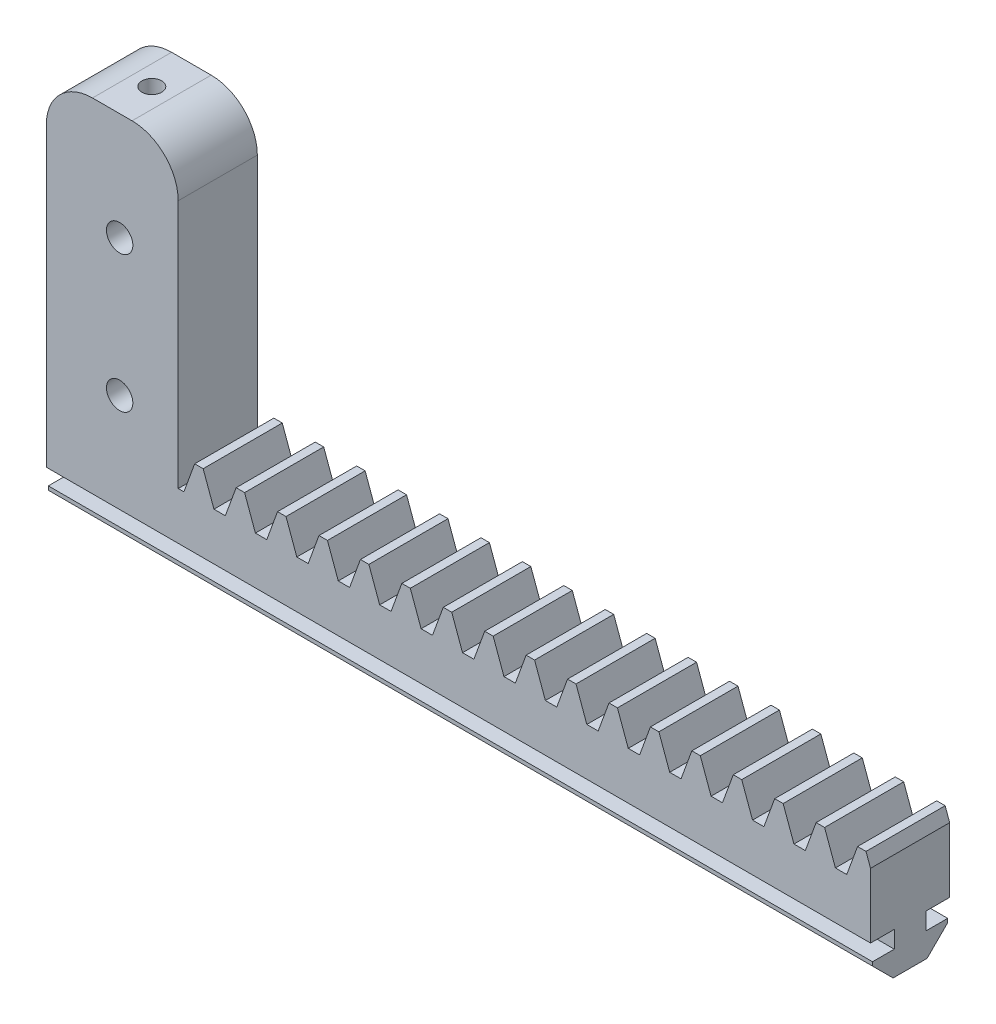
SolidWorks part; units mm, degrees
extrude "Blank" add sketch "BlankSke" against normal blind 12
sketch "BlankSke" plane through (0, 0, 0) normal (0, 0, 1) x (1, 0, 0)
  line L1 (0, 0) -> (105, 0)
  line L2 (0, 0) -> (0, 18)
  line L3 (0, 18) -> (105, 18)
  line L4 (105, 0) -> (105, 18)
  dimension "Length" = 105
  dimension "Blank_height" = 18
material "WhitePLA"
ref_plane "Plane1" through (0, 0, 0) normal (0, 0, 1) x (1, 0, 0)
ref_plane "Plane2" through (0, 0, 0) normal (0, 1, 0) x (1, 0, 0)
ref_plane "Plane3" through (0, 0, 0) normal (1, 0, 0) x (0, 0, -1)
sketch "HoldingSke" plane through (0, 0, 0) normal (0, 1, 0) x (1, 0, 0)
  line L0 (0, 0) -> (0.0696, 0.4951)
  line L1 (-15, 0) -> (100, 0) construction
  line L2 (0, 0) -> (-2.1039, 2.3779)
  line L3 (0, 0) -> (-11.863, 4.5341)
  line L4 (0, 0) -> (8.2133, 2.6687)
  line L5 (0, 0) -> (-23.7986, -8.8762)
  line L6 (0, 0) -> (-10.5278, -7.1032)
  line L9 (-71.009, 38.7566) -> (27.6588, 74.6687)
  line L10 (-76.2, 4.3779) -> (-60.2, 4.3779)
  line L11 (0, 0) -> (-12, 0)
  line L12 (-76.2, 101.6) -> (-76.133, 101.6)
  line L13 (24.9733, 27.94) -> (52.9518, 28.4284)
  line L14 (24.9733, 27.94) -> (24.9743, 27.94)
  line L15 (24.9733, 27.94) -> (100.4006, 29.5858)
  circle A0 centre (0, 0) radius 19.05
  circle A1 centre (0, 0) radius 8
  circle A2 centre (0, 0) radius 12.7
  dimension "MPH" = 16
  dimension "Diameter" = 38.1
  dimension "Num_teeth" = 18
  dimension "Pitch" = 0.5
  dimension "Show_teeth" = 998
  dimension "Thickness" = 12.7
  dimension "Ap" = 20
  dimension "Pitch_height" = 16
  dimension "Width" = 12
  dimension "Backlash" = 0.067
  dimension "Addendum_fac" = 1
  dimension "Dedendum_fac" = 1.25
  dimension "Clearance_fac" = 0.25
  dimension "Dedendum_add" = 0.001
  dimension "Length" = 105
  dimension "Module" = 2
sketch "TooCutSkeIll" plane through (0, 0, 0) normal (0, 0, 1) x (1, 0, 0)
  line L0 (-2.4806, 17.9474) -> (-0.9819, 13.8296)
  line L1 (-0.5111, 13.5) -> (0.5111, 13.5)
  line L2 (0.9819, 13.8296) -> (2.4806, 17.9474)
  line L3 (105, 18) -> (0, 18) construction
  line L4 (0, 0) -> (0, 64.897) construction
  line L5 (-13.208, 16) -> (12.954, 16) construction
  line L6 (0, 0) -> (105, 0) construction
  line L7 (1.7718, 16) -> (1.7718, 48.7463) construction
  line L8 (-1.7718, 16) -> (-1.7718, 48.7463) construction
  line L9 (2.5558, 18) -> (2.5558, 18.0254)
  line L10 (-2.5558, 18) -> (-2.5558, 18.0254)
  line L11 (-2.5558, 18.0254) -> (2.5558, 18.0254)
  arc A0 (0.5111, 13.5) -> (0.9819, 13.8296) centre (0.5111, 14.001) ccw
  arc A1 (-0.9819, 13.8296) -> (-0.5111, 13.5) centre (-0.5111, 14.001) ccw
  arc A2 (2.5558, 18) -> (2.4806, 17.9474) centre (2.5558, 17.92) ccw
  arc A3 (-2.4806, 17.9474) -> (-2.5558, 18) centre (-2.5558, 17.92) ccw
  dimension "Pitch_height" = 16
  dimension "Addendum_plus" = 2.0254
  dimension "Pressure_angle" = 20
  dimension "Gap_width" = 3.5436
  dimension "Dedendum" = 2.5
extrude "ToothCutIll" [suppressed] cut sketch "TooCutSkeIll" against normal through all
sketch "TooCutSkeSim" plane through (0, 0, 0) normal (0, 0, 1) x (1, 0, 0)
  line L0 (0.8619, 13.5) -> (-0.8619, 13.5)
  line L1 (2.509, 18.0254) -> (0.8619, 13.5)
  line L2 (0, 17.4625) -> (0, 53.467) construction
  line L3 (2.509, 18.0254) -> (-2.509, 18.0254)
  line L6 (-2.509, 18.0254) -> (-0.8619, 13.5)
  line L9 (-1.7718, 16) -> (1.7718, 16) construction
  line L10 (0, 0) -> (105, 0) construction
  line L11 (1.7718, 16) -> (1.7718, 53.467) construction
  line L12 (-1.7718, 16) -> (-1.7718, 53.467) construction
  dimension "Pitch_height" = 16
  dimension "Addendum_plus" = 2.0254
  dimension "Pressure_angle" = 20
  dimension "Gap_width" = 3.5436
  dimension "Dedendum" = 2.5
extrude "ToothCutSim" cut sketch "TooCutSkeSim" against normal through all
pattern_linear "TeethCuts" count 17 spacing 6.2832 along (1, 0, 0) of "ToothCutIll", "ToothCutSim"
sketch "Sketch1" plane through (105, 0, 0) normal (1, 0, 0) x (0, 0, -1)
  line L0 (3.4243, 0) -> (0.3, 3.1243)
  line L1 (0.3, 3.1243) -> (0.3, 3.7)
  line L2 (0.3, 3.7) -> (3.6, 3.7)
  line L3 (8.4, 3.7) -> (11.7, 3.7)
  line L4 (11.7, 3.7) -> (11.7, 3.1243)
  line L5 (11.7, 3.1243) -> (8.5757, 0)
  line L6 (3.6, 6.3) -> (0, 6.3)
  line L7 (8.4, 6.3) -> (12, 6.3)
  line L8 (0, 6.3) -> (0, 0)
  line L9 (0, 0) -> (3.4243, 0)
  line L10 (8.5757, 0) -> (12, 0)
  line L11 (8.5757, 0) -> (3.4243, 0)
  line L12 (12, 0) -> (12, 6.3)
  line L13 (3.6, 3.7) -> (3.6, 6.3)
  line L14 (8.4, 6.3) -> (8.4, 3.7)
  line L15 (0, 0) -> (0, 16.1164) construction
  line L16 (0, 16.1164) -> (12, 16.1164) construction
  line M9 (0, 16.1164) -> (0, 0)
  line M10 (0, 0) -> (12, 0)
  line M11 (12, 0) -> (12, 16.1164)
  dimension "D1" = 0.3
  dimension "D2" = 3.4243
  dimension "D3" = 11.7
  dimension "D4" = 9.8164
  dimension "D5" = 12.9921
  dimension "D7" = 12
extrude "Cut-Extrude1" cut sketch "Sketch1" against normal through all contours L2 L13 L6 L0 L1 M9 M10 | L7 L14 L3 L4 L5 M10 M11
sketch "Sketch2" plane through (0, 0, 0) normal (-1, 0, 0) x (0, 0, 1)
  line L0 (-12, 58.3) -> (0, 58.3)
  line L1 (-3.6, 6.3) -> (0, 6.3)
  line L2 (0, 6.3) -> (0, 58.3)
  line L3 (-12, 58.3) -> (-12, 6.3)
  line L4 (-12, 6.3) -> (-8.4, 6.3)
  line L5 (-8.4, 6.3) -> (-8.4, 3.7)
  line L6 (-8.4, 3.7) -> (-11.7, 3.7)
  line L7 (-11.7, 3.7) -> (-11.7, 3.1243)
  line L8 (-11.7, 3.1243) -> (-8.5757, 0)
  line L9 (-8.5757, 0) -> (-3.4243, 0)
  line L10 (-3.4243, 0) -> (-0.3, 3.1243)
  line L11 (-0.3, 3.1243) -> (-0.3, 3.7)
  line L12 (-0.3, 3.7) -> (-3.6, 3.7)
  line L13 (-3.6, 3.7) -> (-3.6, 6.3)
  line L15 (-12, 13.5) -> (0, 13.5) construction
  line L16 (0, 13.5) -> (0, 6.3) construction
  line L17 (-12, 6.3) -> (-12, 16.1164) construction
  dimension "D1" = 52
  dimension "D2" = 52
  dimension "D3" = 9.8
  dimension "D4" = 10.3757
  dimension "D5" = 13.5
extrude "Boss-Extrude1" add sketch "Sketch2" along normal blind 20
fillet "Fillet2" radius 7 2 edges at (0, 58.3, -6) (-20, 58.3, -6)
sketch "Sketch3" plane through (0, 58.3, 0) normal (0, 1, 0) x (1, 0, 0)
  line L0 (-10, 12) -> (-10, 0)
  line L1 (-13, 12) -> (-7, 12) construction
  line L2 (-13, 0) -> (-7, 0) construction
  circle A0 centre (-10, 6) radius 1.5
  dimension "D1" = 3
extrude "Cut-Extrude2" cut sketch "Sketch3" against normal blind 9 contours L0 A0 | L0 A0
ref_plane "Plane4" through (0, 54.3, 0) normal (0, 1, 0) x (1, 0, 0)
sketch "Sketch4" plane through (0, 54.3, 0) normal (0, 1, 0) x (1, 0, 0)
  line L17 (-13.05, 7.7609) -> (-13.05, 6)
  line L18 (-13.05, 6) -> (-13.05, 4.2391)
  line L19 (-13.05, 4.2391) -> (-11.525, 3.3586)
  line L20 (-11.525, 3.3586) -> (-10, 2.4782)
  line L21 (-10, 2.4782) -> (-8.475, 3.3586)
  line L22 (-8.475, 3.3586) -> (-6.95, 4.2391)
  line L23 (-6.95, 4.2391) -> (-6.95, 6)
  line L24 (-6.95, 6) -> (-6.95, 7.7609)
  line L25 (-13.05, 7.7609) -> (-13.05, 12)
  line L26 (-13, 12) -> (-20, 12) construction
  line L27 (-6.95, 7.7609) -> (-6.95, 12)
  line L28 (0, 12) -> (-7, 12) construction
  line L29 (-13.05, 12) -> (-6.95, 12)
  line L37 (-11.25, 6) -> (-8.75, 6)
  circle A0 centre (-10, 6) radius 1.25
  dimension "D1" = 2.5
  dimension "D2" = 6.95
  dimension "D3" = 8.475
  dimension "D4" = 2.4782
  dimension "D5" = 3.3586
extrude "Cut-Extrude3" cut sketch "Sketch4" against normal blind 3
sketch "Sketch5" plane through (0, 0, 0) normal (0, 0, 1) x (1, 0, 0)
  line L0 (-20, 6.3) -> (-20, 51.3)
  line L1 (105, 6.3) -> (105, 16.1164) construction
  line L2 (-13, 58.3) -> (-7, 58.3)
  line L3 (-20, 6.3) -> (105, 6.3) construction
  arc A0 (0, 51.3) -> (-7, 58.3) centre (-7, 51.3) ccw
  arc A1 (-13, 58.3) -> (-20, 51.3) centre (-13, 51.3) ccw
  circle A2 centre (-8.8817, 42) radius 2
  circle A3 centre (-8.8817, 21.3) radius 2
  dimension "D1" = 4
  dimension "D2" = 7
  dimension "D3" = 105
  dimension "D4" = 113.8817
  dimension "D5" = 125
  dimension "D6" = 9.8164
  dimension "D7" = 15
  dimension "D8" = 35.7
  dimension "D9" = 52
extrude "Cut-Extrude4" cut sketch "Sketch5" against normal up to next contours A2 | A3
sketch "Sketch6" plane through (0, 0, 0) normal (0, 0, 1) x (1, 0, 0)
  line L0 (-20, 0) -> (105, 0)
equation "' \"Module@HoldingSke\" = 6.35"
equation "' \"Num_teeth@HoldingSke\" = 12"
equation "' \"Ap@HoldingSke\" =  20"
equation "' \"Ap@HoldingSke\" = 20"
equation "' \"Width@HoldingSke\" = 0.25 * 25.4"
equation "' \"Show_teeth@HoldingSke\" = 500"
equation "' \"Backlash@HoldingSke\" = 0.009 * 25.4"
equation "' \"Addendum_fac@HoldingSke\" = 1.0"
equation "' \"Dedendum_fac@HoldingSke\" = 1.25"
equation "' \"Dedendum_add@HoldingSke\" = 0.00005 * 25.4"
equation "' \"Clearance_fac@HoldingSke\" = 0.25"
equation "' \"Pitch_height@HoldingSke\" = 1 * 25.4"
equation "' \"Length@HoldingSke\" = 4.71 * 25.4"
equation "\"Pitch@HoldingSke\" = 1 / \"Module@HoldingSke\""
equation "\"MPH@HoldingSke\" = \"Dedendum_fac@HoldingSke\" / \"Pitch@HoldingSke\" + 2 * \"Dedendum_add@HoldingSke\" + 0.002 * 25.4"
equation "\"MPH@HoldingSke\" = ((sgn( \"MPH@HoldingSke\" - \"Pitch_height@HoldingSke\")+1)*( \"MPH@HoldingSke\" - \"Pitch_height@HoldingSke\"))/2 + \"Pitch_height@HoldingSke\""
equation "\"Blank_height@BlankSke\" = \"Pitch_height@HoldingSke\" + \"Addendum_fac@HoldingSke\"  / \"Pitch@HoldingSke\" "
equation "\"Length@BlankSke\" =  \"Length@HoldingSke\""
equation "\"Face_width@Blank\" = \"Width@HoldingSke\""
equation "\"Pressure_angle@TooCutSkeIll\" = \"Ap@HoldingSke\""
equation "\"Addendum_plus@TooCutSkeIll\" =  \"Addendum_fac@HoldingSke\"  / \"Pitch@HoldingSke\" + 0.001 *25.4"
equation "\"Dedendum@TooCutSkeIll\" = \"Dedendum_fac@HoldingSke\"  / \"Pitch@HoldingSke\""
equation "\"Pitch_height@TooCutSkeIll\" =  \"MPH@HoldingSke\""
equation "\"Gap_width@TooCutSkeIll\" = 3.14159265 / 2 / \"Pitch@HoldingSke\" + 6 * \"Backlash@HoldingSke\""
equation "\"Pressure_angle@TooCutSkeSim\" = \"Ap@HoldingSke\""
equation "\"Addendum_plus@TooCutSkeSim\" =  \"Addendum_fac@HoldingSke\"  / \"Pitch@HoldingSke\" + 0.001 * 25.4"
equation "\"Dedendum@TooCutSkeSim\" = \"Dedendum_fac@HoldingSke\"  / \"Pitch@HoldingSke\""
equation "\"Pitch_height@TooCutSkeSim\" =  \"MPH@HoldingSke\""
equation "\"Gap_width@TooCutSkeSim\" = 3.14159265 / 2 / \"Pitch@HoldingSke\" + 6 * \"Backlash@HoldingSke\""
equation "\"Root_fillet@TooCutSkeIll\" = \"Clearance_fac@HoldingSke\" / \"Pitch@HoldingSke\" + \"Dedendum_add@HoldingSke\""
equation "\"Break_rad@TooCutSkeIll\" = 0.02 / \"Pitch@HoldingSke\" * 2"
equation "\"Linear_pitch@TeethCuts\" = 3.14159265 / \"Pitch@HoldingSke\""
equation "\"Num_teeth@HoldingSke\" = int( ( \"Length@HoldingSke\" + 0 ) / (3.14159265 / \"Pitch@HoldingSke\")) + 0.9999  + 1"
equation " \"Num_teeth@TeethCuts\" = int( \"Show_teeth@HoldingSke\" ) + 1"
equation " \"Num_teeth@TeethCuts\" = ((sgn( \"Num_teeth@TeethCuts\" - \"Num_teeth@HoldingSke\" )-1)*( \"Num_teeth@TeethCuts\" - \"Num_teeth@HoldingSke\" ))/-2+ \"Num_teeth@HoldingSke\""
equation " \"Num_teeth@TeethCuts\" = ((sgn( \"Num_teeth@TeethCuts\" - 2.0)+1)*( \"Num_teeth@TeethCuts\" - 2.0))/2 +2.0"
